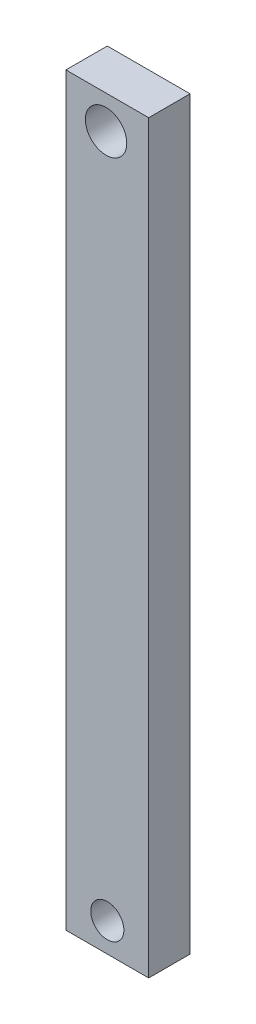
SolidWorks part; units mm, degrees
ref_plane "Front Plane" through (0, 0, 0) normal (0, 0, 1) x (1, 0, 0)
ref_plane "Top Plane" through (0, 0, 0) normal (0, 1, 0) x (1, 0, 0)
ref_plane "Right Plane" through (0, 0, 0) normal (1, 0, 0) x (0, 0, -1)
sketch "Sketch1" plane through (0, 0, 0) normal (0, 0, 1) x (1, 0, 0)
  line L1 (-5.3719, 7.1694) -> (4.6281, 7.1694)
  line L2 (-5.3719, 7.1694) -> (-5.3719, -82.8306)
  line L3 (-5.3719, -82.8306) -> (4.6281, -82.8306)
  line L4 (4.6281, 7.1694) -> (4.6281, -82.8306)
  dimension "D1" = 10
  dimension "D2" = 90
extrude "Boss-Extrude1" add sketch "Sketch1" along normal blind 5
sketch "Sketch2" plane through (0, 0, 5) normal (0, 0, 1) x (1, 0, 0)
  line L4 (4.6281, 7.1694) -> (-5.3719, 7.1694) construction
  line L5 (-5.3719, -82.8306) -> (4.6281, -82.8306) construction
  line L6 (-5.3719, 7.1694) -> (-5.3719, -82.8306) construction
  circle A2 centre (-0.5217, 3.1694) radius 2.5
  circle A3 centre (-0.3719, -79.3306) radius 2
  dimension "D1" = 4
  dimension "D2" = 5
  dimension "D3" = 4
  dimension "D4" = 3.5
  dimension "D5" = 5
extrude "Cut-Extrude1" cut sketch "Sketch2" against normal through all
